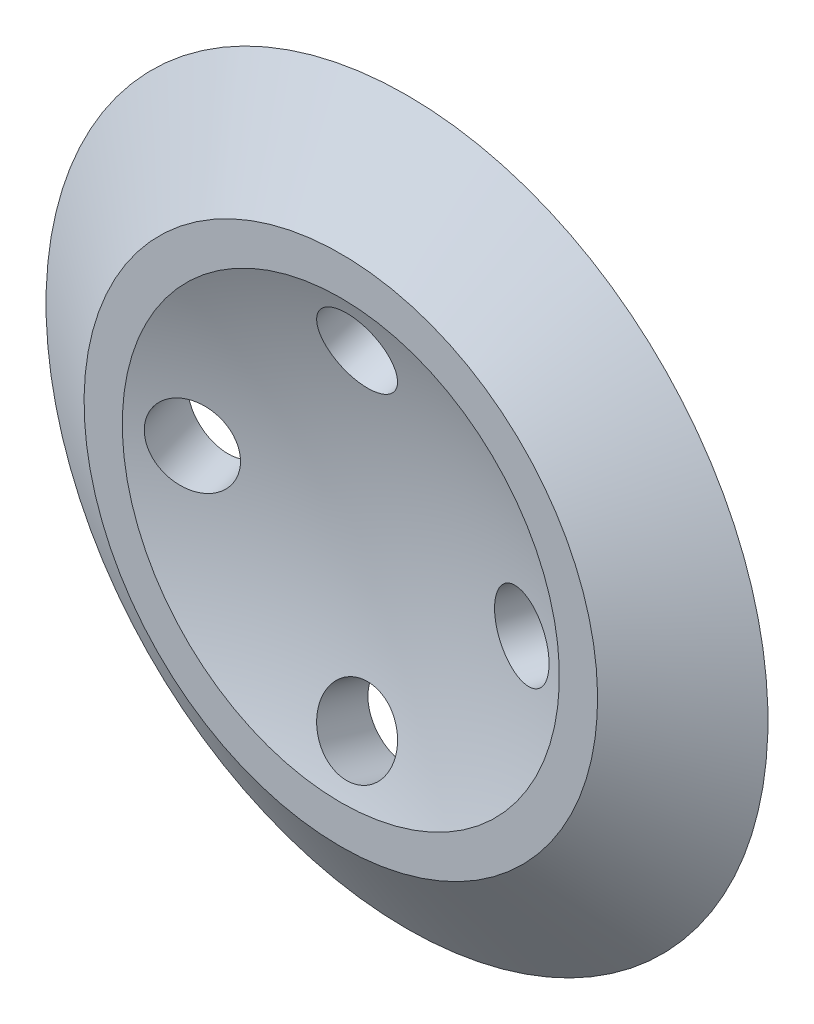
SolidWorks part; units mm, degrees
material "陶瓷"
ref_plane "前视基准面" through (0, 0, 0) normal (0, 0, 1) x (1, 0, 0)
ref_plane "上视基准面" through (0, 0, 0) normal (0, 1, 0) x (1, 0, 0)
ref_plane "右视基准面" through (0, 0, 0) normal (1, 0, 0) x (0, 0, -1)
sketch "草图1" plane through (0, 0, 0) normal (1, 0, 0) x (0, 0, -1)
  line L12 (0, 23.8695) -> (0, -4.3678) construction
  line L25 (0, 0) -> (0, -4.3678)
  line L27 (60, -4.3678) -> (0, -4.3678)
  line L28 (36.3261, 6.6322) -> (42.6795, 6.6322)
  line L30 (42.6795, 6.6322) -> (60, -4.3678)
  arc A1 (0, 0) -> (36.3261, 6.6322) centre (0, 102.8) ccw
  dimension "D11" = 205.6
  dimension "D3" = 11
  dimension "D2" = 60
revolve "旋转1" add sketch "草图1" angle 360 about L12
sketch "草图2" plane through (0, 0, 0) normal (0, 0, 1) x (1, 0, 0)
  line L0 (0, 46.7552) -> (0, -37.8066) construction
  line L1 (0, 99.4096) -> (37.1387, -30.1084) construction
  line L2 (23.1166, 18.7925) -> (29.3648, 20.5841)
  line L3 (29.3648, 20.5841) -> (39.5641, -14.985)
  line L4 (39.5641, -14.985) -> (33.3159, -16.7767)
  line L7 (23.1166, 18.7925) -> (33.3159, -16.7767)
  line L8 (0, 89.2705) -> (0, -48.8197) construction
  circle A0 centre (0, 99.4096) radius 96.5073 construction
  dimension "D1" = 16
  dimension "D3" = 6.5
revolve "切除-旋转1" cut sketch "草图2" angle 360 about L1
pattern_circular "阵列(圆周)1" count 4 over 360 of "切除-旋转1"
move or copy body "实体-移动/复制1" bodies to move or copy 112 copy no rotation origin (0, 1.1322, 0) rotation axis (1, 0, 0) rotation angle 90
